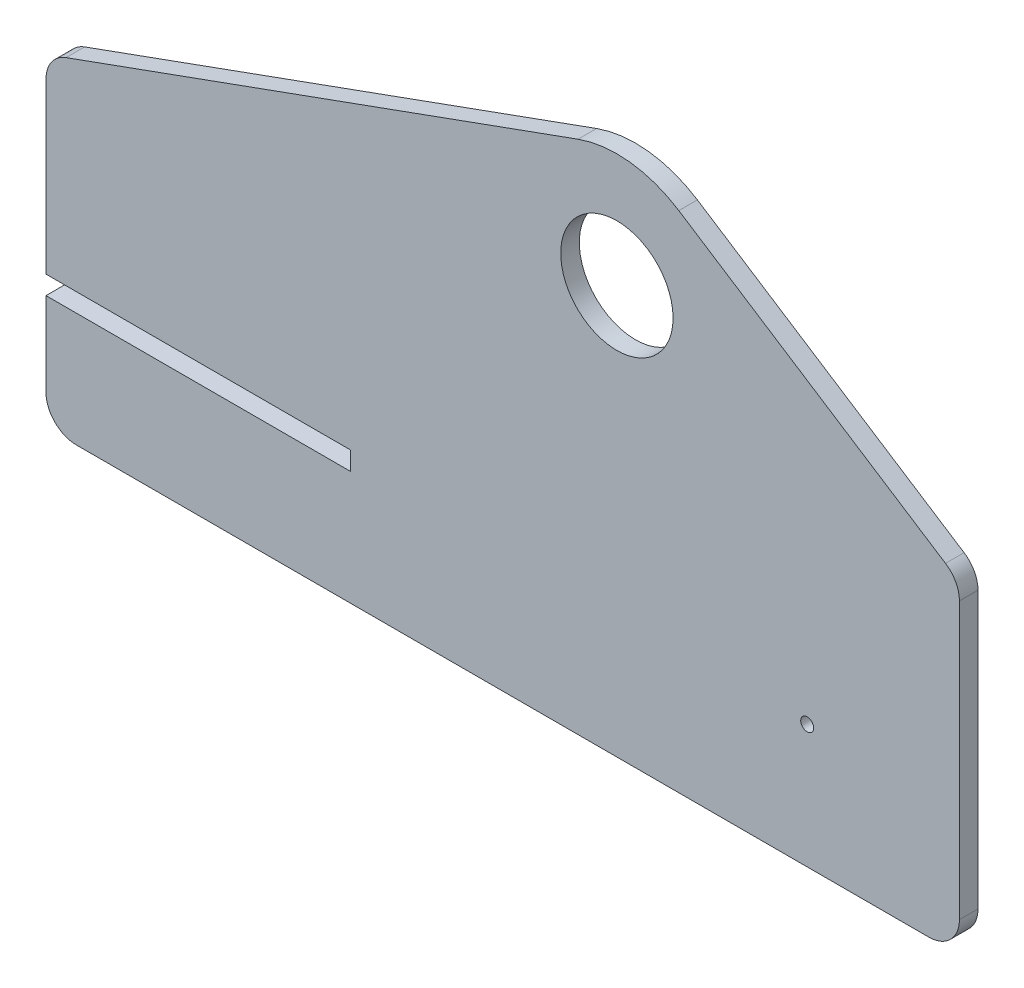
SolidWorks part; units mm, degrees
material "Corrugated Paper"
ref_plane "Front Plane" through (0, 0, 0) normal (0, 0, 1) x (1, 0, 0)
ref_plane "Top Plane" through (0, 0, 0) normal (0, 1, 0) x (1, 0, 0)
ref_plane "Right Plane" through (0, 0, 0) normal (1, 0, 0) x (0, 0, -1)
sketch "Sketch2" plane through (0, 0, 0) normal (0, 0, 1) x (1, 0, 0)
  line L0 (-50.8, 1.5494) -> (-50.8, 7.8994)
  line L1 (-50.8, -7.8994) -> (50.8, -7.8994)
  line L2 (-50.8, -7.8994) -> (-50.8, -1.5494)
  line L3 (-50.8, 7.8994) -> (50.8, 7.8994)
  line L4 (50.8, -7.8994) -> (50.8, 7.8994)
  line L5 (-50.8, -7.8994) -> (50.8, 7.8994) construction
  line L6 (-50.8, 7.8994) -> (50.8, -7.8994) construction
  line L7 (-50.8, 1.5494) -> (0, 1.5494)
  line L9 (-50.8, -1.5494) -> (0, -1.5494)
  line L10 (0, 1.5494) -> (0, -1.5494)
  point P0 (0, 0)
  dimension "D1" = 50.8
  dimension "D3" = 3.0988
  dimension "D2" = 6.35
extrude "Boss-Extrude1" add sketch "Sketch2" along normal blind 3.0988
sketch "Sketch3" plane through (0, 0, 0) normal (0, 0, 1) x (1, 0, 0)
  line L0 (-50.8, -7.8994) -> (-50.8, -20.5994)
  line L1 (-50.8, -20.5994) -> (101.6, -20.5994)
  line L2 (101.6, -20.5994) -> (101.6, 33.2994)
  line L3 (50.8, 7.8994) -> (-50.8, 7.8994) construction
  line L5 (-50.8, 33.2994) -> (-50.8, 7.8994)
  line L6 (-50.8, -7.8994) -> (50.8, -7.8994) construction
  line L7 (50.8, -7.8994) -> (50.8, 7.8994) construction
  line L8 (-50.8, -7.8994) -> (50.8, -7.8994)
  line L9 (50.8, -7.8994) -> (50.8, 7.8994)
  line L10 (50.8, 7.8994) -> (-50.8, 7.8994)
  line L12 (54.7822, 63.5237) -> (101.6, 33.2994)
  line L13 (37.9659, 65.4316) -> (-50.8, 33.2994)
  circle A0 centre (76.2, 0) radius 1.0795
  circle A1 centre (44.45, 47.519) radius 9.3726
  arc A2 (54.7822, 63.5237) -> (37.9659, 65.4316) centre (44.45, 47.519) ccw
  dimension "D1" = 2.159
  dimension "D7" = 38.1
  dimension "D8" = 18.7452
  dimension "D2" = 12.7
  dimension "D3" = 25.4
  dimension "D4" = 152.4
  dimension "D5" = 25.4
  dimension "D6" = 57.15
  dimension "D9" = 31.75
extrude "Boss-Extrude2" add sketch "Sketch3" along normal blind 3.0988
fillet "Fillet1" radius 5.08 4 edges at (101.6, 33.2994, 1.5494) (101.6, -20.5994, 1.5494) (-50.8, -20.5994, 1.5494) (-50.8, 33.2994, 1.5494)
equation "\"rodThick\"= 0.085in"
equation "\"thick\"= 0.122in"
equation "\"clear\"= 0.003in"
equation "\"D3@Sketch2\"=\"thick\""
equation "\"D1@Boss-Extrude1\"=\"thick\""
equation "\"D1@Sketch3\"=\"rodThick\""
equation "\"D1@Boss-Extrude2\"=\"thick\""
